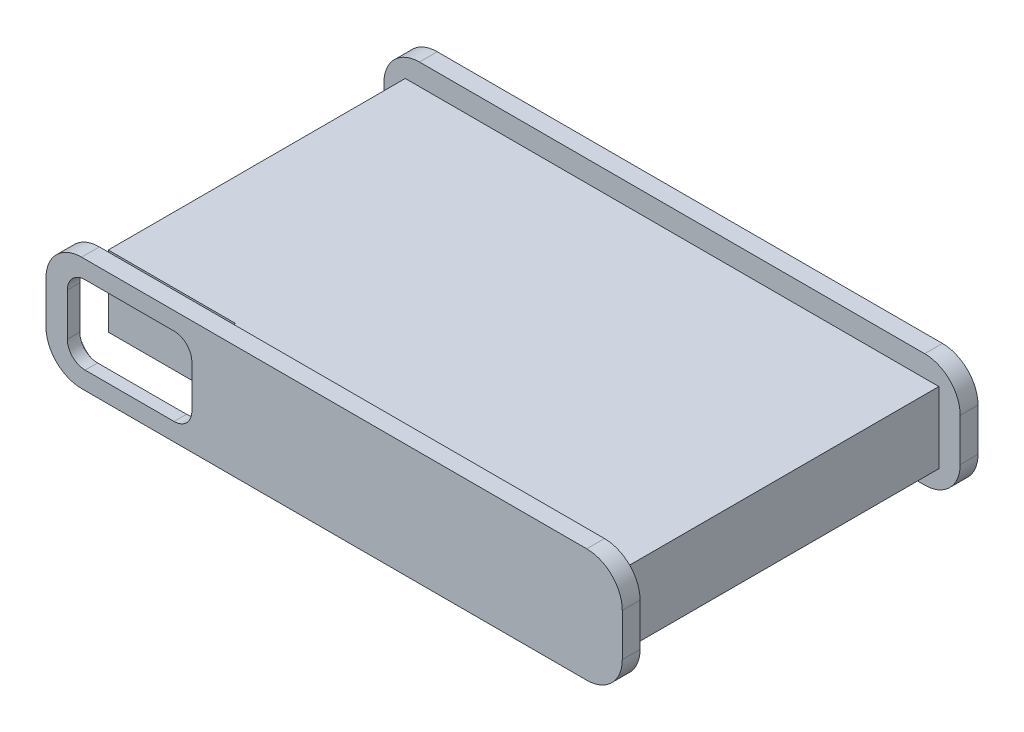
SolidWorks part; units mm, degrees
material "7079 Alloy"
ref_plane "Front Plane" through (0, 0, 0) normal (0, 0, 1) x (1, 0, 0)
ref_plane "Top Plane" through (0, 0, 0) normal (0, 1, 0) x (1, 0, 0)
ref_plane "Right Plane" through (0, 0, 0) normal (1, 0, 0) x (0, 0, -1)
sketch "Sketch1" plane through (0, 0, 0) normal (0, 0, 1) x (1, 0, 0)
  line L1 (-75, 10) -> (75, 10)
  line L2 (-75, 10) -> (-75, -10)
  line L3 (-75, -10) -> (75, -10)
  line L4 (75, 10) -> (75, -10)
  line L5 (0, -10) -> (0, 10) construction
  line L6 (-75, 0) -> (75, 0) construction
  point P0 (0, 0)
  dimension "D1" = 20
  dimension "D2" = 150
extrude "Boss-Extrude1" add sketch "Sketch1" along normal blind 90
sketch "Sketch2" plane through (0, 0, 0) normal (0, 0, -1) x (-1, 0, 0)
  line L0 (-81, 16) -> (-81, -16)
  line L5 (-81, -16) -> (81, -16)
  line L6 (81, -16) -> (81, 16)
  line L7 (81, 16) -> (-81, 16)
  line L8 (-75, 10) -> (-75, -10)
  line L9 (-75, -10) -> (75, -10)
  line L10 (75, -10) -> (75, 10)
  line L11 (75, 10) -> (-75, 10)
  line L12 (-75, 10) -> (-75, -10) construction
  line L13 (-75, -10) -> (75, -10) construction
  line L14 (75, -10) -> (75, 10) construction
  line L15 (75, 10) -> (-75, 10) construction
  dimension "D1" = 0
  dimension "D2" = 6
extrude "Boss-Extrude2" add sketch "Sketch2" along normal blind 5
fillet "Fillet1" radius 10 1 edges at (81, 16, -2.5)
fillet "Fillet2" radius 10 1 edges at (81, -16, -2.5)
fillet "Fillet3" radius 10 1 edges at (-81, 16, -2.5)
fillet "Fillet4" radius 10 1 edges at (-81, -16, -2.5)
sketch "Sketch3" plane through (0, 0, 90) normal (0, 0, 1) x (1, 0, 0)
  line L4 (-81, 6) -> (-81, -6)
  line L5 (-71, -16) -> (71, -16)
  line L6 (81, -6) -> (81, 6)
  line L7 (71, 16) -> (-71, 16)
  line L8 (-81, 6) -> (-81, -6)
  line L9 (-71, -16) -> (71, -16)
  line L10 (81, -6) -> (81, 6)
  line L11 (71, 16) -> (-71, 16)
  arc A4 (-81, -6) -> (-71, -16) centre (-71, -6) ccw
  arc A5 (71, -16) -> (81, -6) centre (71, -6) ccw
  arc A6 (81, 6) -> (71, 16) centre (71, 6) ccw
  arc A7 (-71, 16) -> (-81, 6) centre (-71, 6) ccw
  arc A8 (-81, -6) -> (-71, -16) centre (-71, -6) ccw
  arc A9 (71, -16) -> (81, -6) centre (71, -6) ccw
  arc A10 (81, 6) -> (71, 16) centre (71, 6) ccw
  arc A11 (-71, 16) -> (-81, 6) centre (-71, 6) ccw
  dimension "D1" = 0
extrude "Boss-Extrude3" add sketch "Sketch3" along normal blind 5
sketch "Sketch4" plane through (0, 0, 95) normal (0, 0, 1) x (1, 0, 0)
  line L1 (-70, -11) -> (-45, -11)
  line L2 (-75, -6) -> (-75, 6)
  line L3 (-70, 11) -> (-45, 11)
  line L4 (-40, -6) -> (-40, 6)
  line L5 (-57.5, 11) -> (-57.5, -11) construction
  line L6 (-75, 0) -> (-40, 0) construction
  arc A0 (-45, -11) -> (-40, -6) centre (-45, -6) ccw
  arc A1 (-45, 11) -> (-40, 6) centre (-45, 6) cw
  arc A2 (-70, -11) -> (-75, -6) centre (-70, -6) cw
  arc A3 (-75, 6) -> (-70, 11) centre (-70, 6) cw
  point P0 (-57.5, 0)
  point P4 (0, 0)
  point P7 (-40, -11)
  point P11 (-40, 11)
  point P16 (-75, 11)
  dimension "D4" = 5
  dimension "D1" = 35
  dimension "D2" = 22
  dimension "D3" = 40
extrude "Cut-Extrude1" cut sketch "Sketch4" against normal blind 3.5
sketch "Sketch5" plane through (0, 0, 91.5) normal (0, 0, 1) x (1, 0, 0)
  line L0 (-77, 6) -> (-77, -6)
  line L1 (-70, -13) -> (-45, -13)
  line L2 (-38, -6) -> (-38, 6)
  line L3 (-45, 13) -> (-70, 13)
  line L4 (-40, -6) -> (-40, 6)
  line L5 (-45, 11) -> (-70, 11)
  line L6 (-75, 6) -> (-75, -6)
  line L7 (-70, -11) -> (-45, -11)
  line L8 (-40, -6) -> (-40, 6) construction
  line L9 (-45, 11) -> (-70, 11) construction
  line L10 (-75, 6) -> (-75, -6) construction
  line L11 (-70, -11) -> (-45, -11) construction
  arc A0 (-70, 13) -> (-77, 6) centre (-70, 6) ccw
  arc A1 (-77, -6) -> (-70, -13) centre (-70, -6) ccw
  arc A2 (-45, -13) -> (-38, -6) centre (-45, -6) ccw
  arc A3 (-38, 6) -> (-45, 13) centre (-45, 6) ccw
  arc A4 (-45, -11) -> (-40, -6) centre (-45, -6) ccw
  arc A5 (-40, 6) -> (-45, 11) centre (-45, 6) ccw
  arc A6 (-70, 11) -> (-75, 6) centre (-70, 6) ccw
  arc A7 (-75, -6) -> (-70, -11) centre (-70, -6) ccw
  arc A8 (-45, -11) -> (-40, -6) centre (-45, -6) ccw construction
  arc A9 (-40, 6) -> (-45, 11) centre (-45, 6) ccw construction
  arc A10 (-70, 11) -> (-75, 6) centre (-70, 6) ccw construction
  arc A11 (-75, -6) -> (-70, -11) centre (-70, -6) ccw construction
  dimension "D1" = 0
  dimension "D2" = 2
extrude "Cut-Extrude2" cut sketch "Sketch5" against normal blind 8
